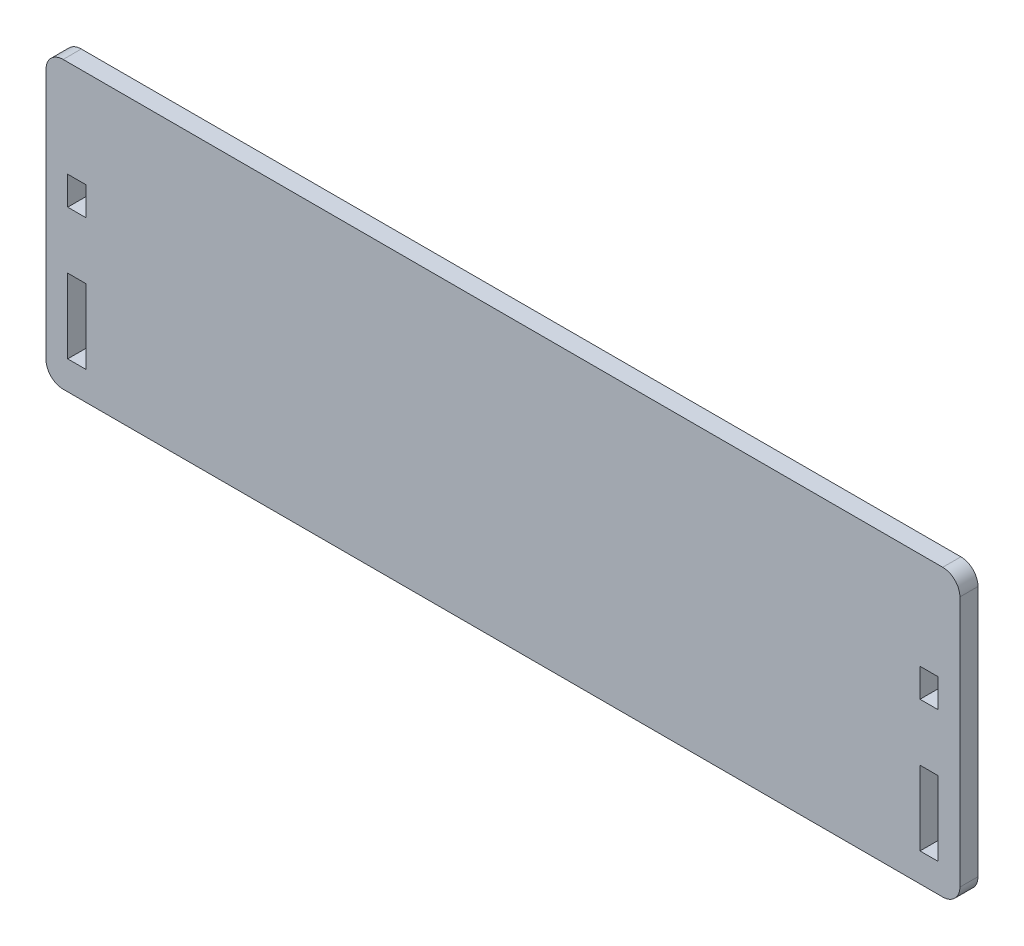
SolidWorks part; units mm, degrees
ref_plane "Front Plane" through (0, 0, 0) normal (0, 0, 1) x (1, 0, 0)
ref_plane "Top Plane" through (0, 0, 0) normal (0, 1, 0) x (1, 0, 0)
ref_plane "Right Plane" through (0, 0, 0) normal (1, 0, 0) x (0, 0, -1)
sketch "Sketch1" plane through (0, 0, 0) normal (0, 0, 1) x (1, 0, 0)
  line L0 (-76.2, -25) -> (76.2, -25)
  line L1 (-80, 25) -> (80, 25)
  line L2 (-80, 25) -> (-80, -25)
  line L3 (-80, -25) -> (80, -25)
  line L4 (80, 25) -> (80, -25)
  line L6 (76.2, -7) -> (76.2, -20)
  line L7 (-80, 25) -> (-80, 8)
  line L8 (-76.2, -20) -> (-76.2, -7)
  line L9 (73.025, -20) -> (76.2, -20)
  line L10 (-76.2, 8) -> (-76.2, 3)
  line L11 (73.025, -7) -> (73.025, -20)
  line L12 (-80, 3) -> (-80, -7)
  line L13 (76.2, -7) -> (73.025, -7)
  line L14 (-76.2, -7) -> (-76.2, -20)
  line L15 (-76.2, 8) -> (-73.025, 8)
  line L16 (-73.025, 8) -> (-73.025, 3)
  line L17 (-73.025, 3) -> (-76.2, 3)
  line L18 (-76.2, -7) -> (-73.025, -7)
  line L19 (-73.025, -7) -> (-73.025, -20)
  line L20 (-73.025, -20) -> (-76.2, -20)
  line L21 (-76.2, 3) -> (-76.2, 8)
  line L24 (-80, 25) -> (-80, -25)
  line L25 (80, 25) -> (80, -25)
  line L26 (73.025, 3) -> (76.2, 3)
  line L27 (76.2, 8) -> (76.2, 3)
  line L28 (76.2, 8) -> (73.025, 8)
  line L29 (73.025, 8) -> (73.025, 3)
  point P0 (0, 0)
  point P9 (0, -25)
  dimension "D8" = 3.175
extrude "Boss-Extrude1" add sketch "Sketch1" along normal blind 3.175 contours L4 L1 L2 L3 L0 L29 L28 L27 L26 L13 L6 L9 L11 L16 L17 L10 L15 L19 L20 L8 L18
fillet "Fillet2" radius 3 1 edges at (-80, 25, 1.5875)
fillet "Fillet3" radius 3 3 edges at (-80, -25, 1.5875) (80, -25, 1.5875) (80, 25, 1.5875)
